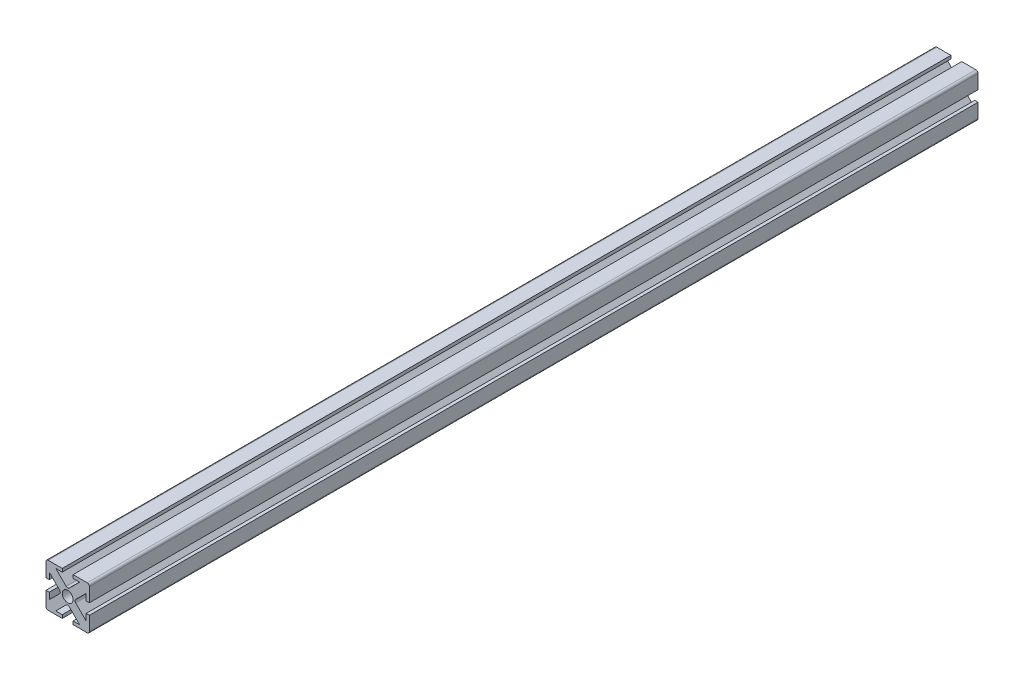
SolidWorks part; units mm, degrees
ref_plane "前基準面" through (0, 0, 0) normal (0, 0, 1) x (1, 0, 0)
ref_plane "上基準面" through (0, 0, 0) normal (0, 1, 0) x (1, 0, 0)
ref_plane "右基準面" through (0, 0, 0) normal (1, 0, 0) x (0, 0, -1)
sketch "草圖1" plane through (0, 0, 0) normal (0, 0, 1) x (1, 0, 0)
  line L0 (-2500, 10000) -> (-2500, 8500)
  line L1 (-10000, 10000) -> (-2500, 10000)
  line L2 (-10000, 10000) -> (-10000, 2500)
  line L3 (-10000, -10000) -> (-2500, -10000)
  line L4 (10000, 10000) -> (10000, 2500)
  line L5 (-10000, 10000) -> (10000, -10000) construction
  line L6 (-10000, -10000) -> (10000, 10000) construction
  line L7 (-2500, 8500) -> (-5500, 8500)
  line L8 (-5500, 8500) -> (0, 3000)
  line L9 (0, 3000) -> (5500, 8500)
  line L10 (5500, 8500) -> (2500, 8500)
  line L11 (2500, 8500) -> (2500, 10000)
  line L12 (0, 10000) -> (0, -11814.1698) construction
  line L13 (8500, 2500) -> (8500, 5500)
  line L14 (8500, -2500) -> (10000, -2500)
  line L15 (10000, 2500) -> (8500, 2500)
  line L16 (8500, 5500) -> (3000, 0)
  line L17 (3000, 0) -> (8500, -5500)
  line L18 (8500, -5500) -> (8500, -2500)
  line L19 (2500, -8500) -> (5500, -8500)
  line L20 (-2500, -8500) -> (-2500, -10000)
  line L21 (2500, -10000) -> (2500, -8500)
  line L22 (5500, -8500) -> (0, -3000)
  line L23 (0, -3000) -> (-5500, -8500)
  line L24 (-5500, -8500) -> (-2500, -8500)
  line L25 (-8500, -2500) -> (-8500, -5500)
  line L26 (-8500, 2500) -> (-10000, 2500)
  line L27 (-10000, -2500) -> (-8500, -2500)
  line L28 (-8500, -5500) -> (-3000, 0)
  line L29 (-3000, 0) -> (-8500, 5500)
  line L30 (-8500, 5500) -> (-8500, 2500)
  line L31 (2500, 10000) -> (10000, 10000)
  line L32 (10000, -2500) -> (10000, -10000)
  line L33 (2500, -10000) -> (10000, -10000)
  line L34 (-10000, -2500) -> (-10000, -10000)
  circle A0 centre (0, 0) radius 2500
  point P0 (0, 0)
  point P41 (0, 0)
  dimension "D3" = 5000
  dimension "D2" = 20000
  dimension "D4" = 5000
  dimension "D5" = 3000
  dimension "D6" = 1500
  dimension "D7" = 4
extrude "填料-伸長1" add sketch "草圖1" along normal blind 410000
fillet "圓角1" radius 1000 4 edges at (0, -3000, 205000) (-3000, 0, 205000) (3000, 0, 205000) (0, 3000, 205000)
fillet "圓角2" radius 1000 4 edges at (-10000, 10000, 205000) (10000, 10000, 205000) (10000, -10000, 205000) (-10000, -10000, 205000)
